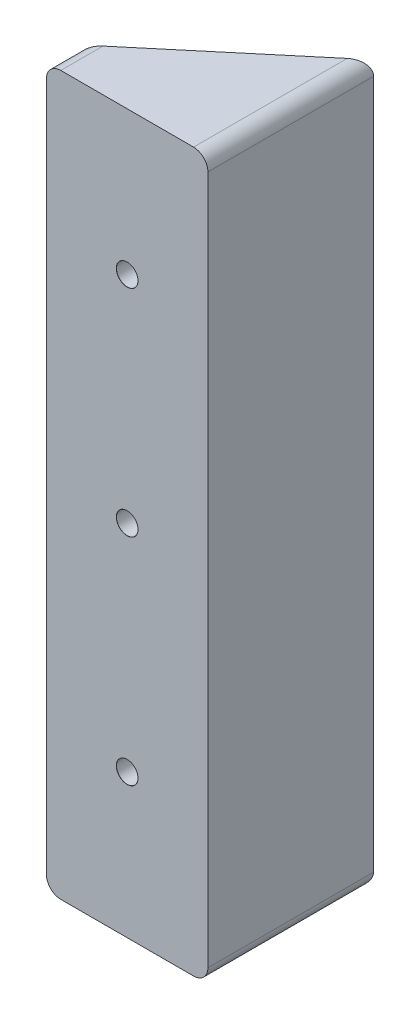
SolidWorks part; units mm, degrees
material "Beech"
ref_plane "Front Plane" through (0, 0, 0) normal (0, 0, 1) x (1, 0, 0)
ref_plane "Top Plane" through (0, 0, 0) normal (0, 1, 0) x (1, 0, 0)
ref_plane "Right Plane" through (0, 0, 0) normal (1, 0, 0) x (0, 0, -1)
sketch "Sketch1" plane through (0, 0, 0) normal (0, 0, 1) x (1, 0, 0)
  line L0 (-31.1883, 134.2727) -> (-31.1883, -65.7273)
  line L1 (-31.1883, -65.7273) -> (13.8117, -65.7273)
  line L2 (-31.1883, 134.2727) -> (13.8117, 134.2727)
  line L3 (13.8117, 134.2727) -> (13.8117, -65.7273)
extrude "Boss-Extrude1" add sketch "Sketch1" along normal blind 500
fillet "Fillet1" radius 4 4 edges at (-31.1883, -65.7273, 250) (13.8117, -65.7273, 250) (-31.1883, 134.2727, 250) (13.8117, 134.2727, 250)
sketch "Sketch4" plane through (0, 134.2727, 0) normal (0, 1, 0) x (1, 0, 0)
  line L0 (-31.1883, -479.5702) -> (13.8117, -500)
  line L1 (-31.1883, -500) -> (-31.1883, 0) construction
extrude "Cut-Extrude3" cut sketch "Sketch4" against normal through all and the other way through all flip side to cut
sketch "Sketch5" plane through (0, 134.2727, 0) normal (0, 1, 0) x (1, 0, 0)
  line L0 (13.8117, 0) -> (-31.1883, -38.7839)
  line L1 (-31.1883, -479.5702) -> (-31.1883, 0) construction
extrude "Cut-Extrude4" cut sketch "Sketch5" against normal through all and the other way through all flip side to cut
sketch "Sketch6" plane through (0, 134.2727, 0) normal (0, 1, 0) x (1, 0, 0)
  line L0 (-31.1883, -38.7839) -> (13.8117, -1.0272)
  line L1 (13.8117, 0) -> (13.8117, -500) construction
  line L2 (576.1812, 470.8968) -> (-726.0486, -621.8966) construction
extrude "Cut-Extrude5" cut sketch "Sketch6" against normal through all and the other way through all
fillet "Fillet2" [suppressed] radius 2
sketch "Sketch7" plane through (0, -65.7273, 0) normal (0, -1, 0) x (-1, 0, 0)
  line L0 (31.1883, -47.1851) -> (-13.8117, -47.1851)
  line L1 (31.1883, -38.7839) -> (31.1883, -479.5702) construction
  line L2 (-13.8117, -500) -> (-13.8117, -1.0272) construction
extrude "Cut-Extrude7" cut sketch "Sketch7" against normal through all and the other way through all
hole_wizard "Ø6.0mm Dowel Slot" positions "Sketch12" profile "Sketch13" size "Ø6.0" standard "ISO" slot yes
sketch "Sketch12" plane through (1239.1617, 134.2727, 47.1851) normal (0, 0, 1) x (-1, 0, 0)
  line L1 (1244.85, 160) -> (1250.85, 160) construction
  point P0 (1247.85, 160)
  point P2 (1247.85, 100)
  point P4 (1247.85, 40)
sketch "Sketch13" plane through (-8.6883, -25.7273, 47.1851) normal (1, 0, 0) x (0, -1, 0)
  line L0 (0, 0) -> (0, 130)
  line L1 (0, 130) -> (3, 128.1974)
  line L2 (3, 128.1974) -> (3, 0.025)
  line L3 (3, 0.025) -> (3.025, 0)
  line L4 (3.025, 0) -> (0, 0)
  line L5 (-3, 0.025) -> (-3.025, 0) construction
  line L6 (0, 130) -> (-3, 128.1974) construction
  line L7 (0, -6.35) -> (0, 107.95) construction
  dimension "Hole Dia." = 6
  dimension "Hole Depth" = 130
  dimension "Near C'Sink Dia." = 6.05
  dimension "Near C'Sink Angle" = 90
  dimension "Drill Angle" = 118
hole_wizard "Ø6.0mm Dowel Slot1" [suppressed] positions "Sketch14" profile "Sketch15" size "Ø6.0" standard "ISO"
sketch "Sketch14" plane through (769.9579, -77.7273, -689.3614) normal (0, -1, 0) x (0.6428, 0, 0.7661)
  point P0 (22.5608, -1722.5)
  point P3 (120.5996, -1722.5)
  point P7 (217.974, -1722.5)
  point P9 (314.7913, -1722.5)
  point P11 (412.5608, -1722.5)
  point P13 (510.3116, -1722.5)
  point P15 (607.5219, -1722.5)
  point P17 (704.9775, -1722.5)
  point P19 (802.5608, -1722.5)
  point P22 (802.5608, -1458.5)
  point P26 (802.5608, -1546.5)
  point P28 (802.5608, -1634.5)
  point P30 (22.5608, -1546.5)
  point P34 (22.5608, -1458.5)
  point P36 (22.5608, -1634.5)
  point P38 (22.5608, -932.5)
  point P41 (-22.4962, -917.6022)
  point P44 (71.2428, -861.25)
  point P48 (120.5996, -883.75)
  point P52 (169.2328, -861.25)
  point P54 (217.974, -883.75)
  point P56 (268.0506, -861.25)
  point P58 (314.7913, -883.75)
  point P60 (364.7201, -861.25)
  point P62 (414.2928, -883.75)
  point P64 (462.5664, -861.25)
  point P66 (511.551, -883.75)
  point P68 (560.2153, -861.25)
  point P70 (657.9263, -861.25)
  point P72 (609.5282, -883.75)
  point P74 (707.1553, -883.75)
  point P76 (755.5069, -861.25)
  point P78 (802.5608, -932.5)
  point P80 (847.4962, -917.6022)
  point P83 (927.0078, -850.8784)
  point P86 (1006.7507, -783.9604)
  point P90 (1086.3394, -717.1719)
  point P93 (802.5608, -761.25)
  point P96 (802.5608, -664.25)
  point P99 (1166.0052, -650.3187)
  point P102 (1185.001, -609.0604)
  point P105 (1185.001, -511.1051)
  point P109 (1185.001, -409.0604)
  point P112 (1185.001, -309.1708)
  point P114 (1185.001, -209.0363)
  point P116 (1185.001, -109.0604)
  point P119 (1185.001, -9.0604)
  point P122 (1021.9151, 22.5)
  point P125 (1024.5, 67.5)
  point P128 (1133.73, 67.5)
  point P131 (1133.73, 22.5)
  point P134 (913.5, 67.5)
  point P137 (910.7185, 22.5)
  point P141 (802.5, 67.5)
  point P147 (802.5, 22.5)
  point P149 (688.5, 67.5)
  point P152 (688.5, 22.5)
  point P154 (577.5192, 67.5)
  point P156 (577.9151, 22.5)
  point P159 (466.3273, 67.5)
  point P161 (466.3273, 22.5)
  point P163 (355.5, 67.5)
  point P166 (355.9151, 22.5)
  point P169 (244.5, 67.5)
  point P172 (244.5, 22.5)
  point P174 (133.5309, 67.5)
  point P176 (133.5309, 22.5)
  point P178 (22.5608, 67.5)
  point P180 (22.5608, 22.5)
  point P182 (-87.7299, 67.5)
  point P184 (-88.0849, 22.5)
  point P187 (-199.0849, 67.5)
  point P190 (-199.0849, 22.5)
  point P193 (-310.0849, 22.5)
  point P196 (-310.0849, 67.5)
  point P199 (-341.0052, -650.3187)
  point P202 (-261.3394, -717.1719)
  point P205 (-181.7507, -783.9604)
  point P209 (-102.0078, -850.8784)
  point P211 (22.5608, -77.5)
  point P214 (22.5608, -179.25)
  point P217 (22.5608, -275.9132)
  point P219 (22.5608, -373.0681)
  point P221 (22.5608, -469.6127)
  point P223 (22.5608, -567.3178)
  point P225 (22.5608, -664.25)
  point P228 (22.5608, -761.25)
  point P231 (802.5608, 167.5)
  point P234 (1185.001, 190.9134)
  point P236 (1185.001, 90.9396)
  point P239 (1185.001, 290.9396)
  point P242 (1185.001, 390.9396)
  point P245 (1185.001, 491.2681)
  point P247 (1185.001, 590.9396)
  point P250 (1185.001, 699.7184)
  point P253 (1166.0052, 740.3187)
  point P256 (1086.3394, 807.1719)
  point P259 (1006.7507, 873.9604)
  point P263 (927.0078, 940.8784)
  point P266 (847.4962, 1007.6022)
  point P269 (802.5608, 1022.8195)
  point P271 (802.5608, 973.75)
  point P274 (802.5608, 951.25)
  point P277 (755.5069, 973.75)
  point P281 (802.5608, 852.5)
  point P284 (707.1553, 951.25)
  point P288 (657.9263, 973.75)
  point P290 (609.5282, 951.25)
  point P292 (560.2153, 973.75)
  point P294 (511.5608, 951.25)
  point P297 (462.5664, 973.75)
  point P299 (412.5608, 951.25)
  point P301 (364.7108, 973.75)
  point P304 (315.9608, 951.25)
  point P307 (266.9108, 973.75)
  point P310 (218.1608, 951.25)
  point P313 (169.1108, 973.75)
  point P316 (120.3608, 951.25)
  point P319 (71.3108, 973.75)
  point P322 (22.5608, 973.75)
  point P325 (22.5608, 1022.5)
  point P328 (22.5608, 951.25)
  point P331 (-102.0078, 940.8784)
  point P334 (-181.7507, 873.9604)
  point P338 (-22.4962, 1007.6022)
  point P341 (-261.3394, 807.1719)
  point P343 (-341.0052, 740.3187)
  point P346 (-360, 699.5681)
  point P349 (-360, 590.9396)
  point P353 (-360, 491.2681)
  point P355 (-360, 390.9396)
  point P357 (-360, 290.9396)
  point P359 (-360, 190.9134)
  point P361 (-360, 90.9396)
  point P363 (-360, -11.9775)
  point P365 (-360, -77.5)
  point P367 (-360, -179.25)
  point P369 (-360, -275.9132)
  point P371 (-360, -373.0681)
  point P373 (-360, -469.6127)
  point P375 (-360, -609.5213)
  point P378 (22.5608, 1812.5)
  point P381 (71.3108, 1812.5)
  point P383 (120.3608, 1812.5)
  point P385 (169.1108, 1812.5)
  point P387 (218.1608, 1812.5)
  point P389 (266.9108, 1812.5)
  point P391 (315.9608, 1812.5)
  point P393 (364.7108, 1812.5)
  point P395 (412.5608, 1812.5)
  point P397 (462.5664, 1812.5)
  point P399 (511.5608, 1812.5)
  point P401 (577.5192, 1812.5)
  point P403 (657.9263, 1812.5)
  point P405 (755.5069, 1812.5)
  point P407 (22.5, 1724.66)
  point P410 (22.5608, 1636.4608)
  point P412 (802.5608, 1812.5)
  point P415 (802.5, 1724.66)
  point P418 (802.5608, 1636.4608)
  point P420 (802.5608, 1548.5146)
  point P432 (22.5608, 851.2226)
  point P434 (22.5608, 754.3426)
  point P436 (22.5608, 657.4768)
  point P438 (22.5608, 559.5838)
  point P440 (22.5608, 463.0035)
  point P442 (22.5608, 365.956)
  point P444 (22.5608, 269.1268)
  point P446 (22.5608, 167.5)
sketch "Sketch15" plane through (2104.0115, -77.7273, -1779.2312) normal (1, 0, 0) x (0, 0, -1)
  line L0 (0, 0) -> (0, 30)
  line L1 (0, 30) -> (3, 28.1974)
  line L2 (3, 28.1974) -> (3, 0.025)
  line L3 (3, 0.025) -> (3.025, 0)
  line L4 (3.025, 0) -> (0, 0)
  line L5 (-3, 0.025) -> (-3.025, 0) construction
  line L6 (0, 30) -> (-3, 28.1974) construction
  line L7 (0, -6.35) -> (0, 107.95) construction
  dimension "Hole Dia." = 6
  dimension "Hole Depth" = 30
  dimension "Near C'Sink Dia." = 6.05
  dimension "Near C'Sink Angle" = 90
  dimension "Drill Angle" = 118
